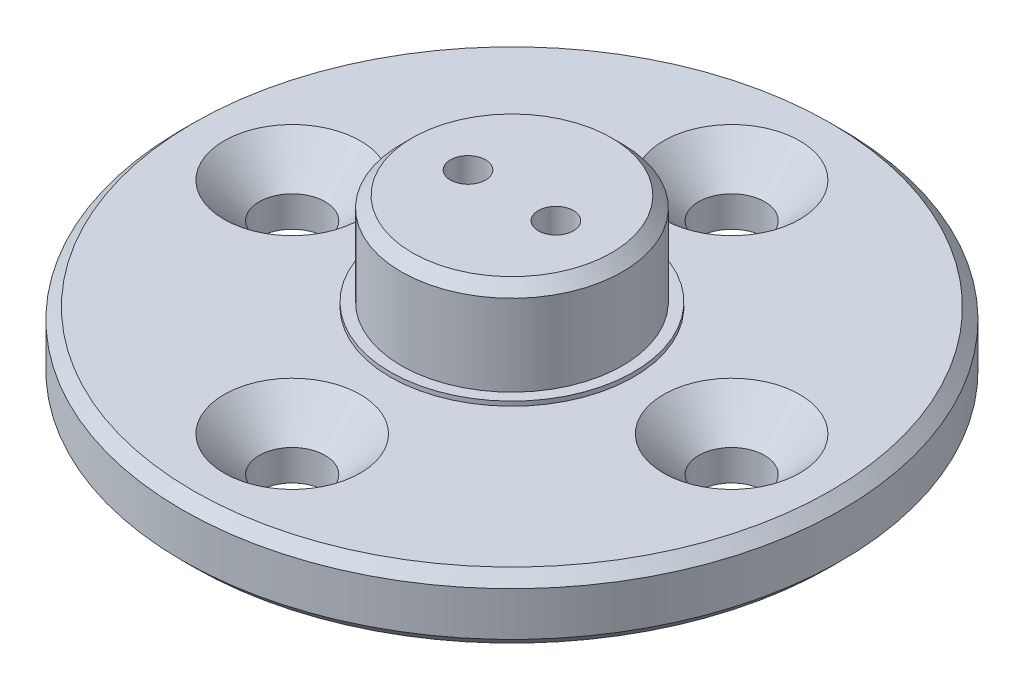
SolidWorks part; units mm, degrees
ref_plane "前视基准面" through (0, 0, 0) normal (0, 0, 1) x (1, 0, 0)
ref_plane "上视基准面" through (0, 0, 0) normal (0, 1, 0) x (1, 0, 0)
ref_plane "右视基准面" through (0, 0, 0) normal (1, 0, 0) x (0, 0, -1)
other "Configuration Table"
sketch "草图1" plane through (0, 0, 0) normal (0, 1, 0) x (1, 0, 0)
  line L0 (-21.98, 0) -> (22.6908, 0) construction
  line L1 (0, 22.7485) -> (0, -21.9381) construction
  circle A0 centre (0, 0) radius 15
  circle A1 centre (0, 10) radius 1.5
  circle A2 centre (10, 0) radius 1.5
  circle A3 centre (0, -10) radius 1.5
  circle A4 centre (-10, 0) radius 1.5
  point P15 (0, 0)
  dimension "D1" = 3
  dimension "D3" = 30
  dimension "D2" = 10
extrude "凸台-拉伸1" add sketch "草图1" along normal blind 3
sketch "草图2" plane through (0, 3, 0) normal (0, 1, 0) x (1, 0, 0)
  line L0 (0, 1.9211) -> (0, -1.7964) construction
  line L1 (-1.959, 0) -> (1.7076, 0) construction
  circle A1 centre (0, 0) radius 5.035
  circle A3 centre (2, 0) radius 0.8
  circle A4 centre (-2, 0) radius 0.8
  dimension "D1" = 10.07
  dimension "D2" = 1.6
  dimension "D3" = 4
extrude "凸台-拉伸2" add sketch "草图2" along normal blind 4.4
sketch "草图4" plane through (0, 3, 0) normal (0, 1, 0) x (1, 0, 0)
  circle A8 centre (0, 0) radius 5.535
  circle A9 centre (0, 0) radius 5.035 construction
  point P15 (0, 0)
  dimension "D1" = 0.5
extrude "凸台-拉伸3" add sketch "草图4" along normal blind 0.2
chamfer "倒角1" distance 0.5 angle 45 1 edges at (0, 7.4, 5.035)
chamfer "倒角3" distance 0.5 angle 45 2 edges at (0, 0, 15) (0, 3, 15)
chamfer "倒角4" distance 1.6 angle 45 4 edges at (10, 3, 1.5) (0, 3, 11.5) (-10, 3, 1.5) (0, 3, -8.5)
sketch "草图5" plane through (0, 7.4, 0) normal (0, 1, 0) x (1, 0, 0)
  circle A0 centre (2, 0) radius 0.8 construction
  circle A1 centre (-2, 0) radius 0.8 construction
  circle A2 centre (2, 0) radius 0.8
  circle A3 centre (-2, 0) radius 0.8
extrude "切除-拉伸1" cut sketch "草图5" against normal blind 10
